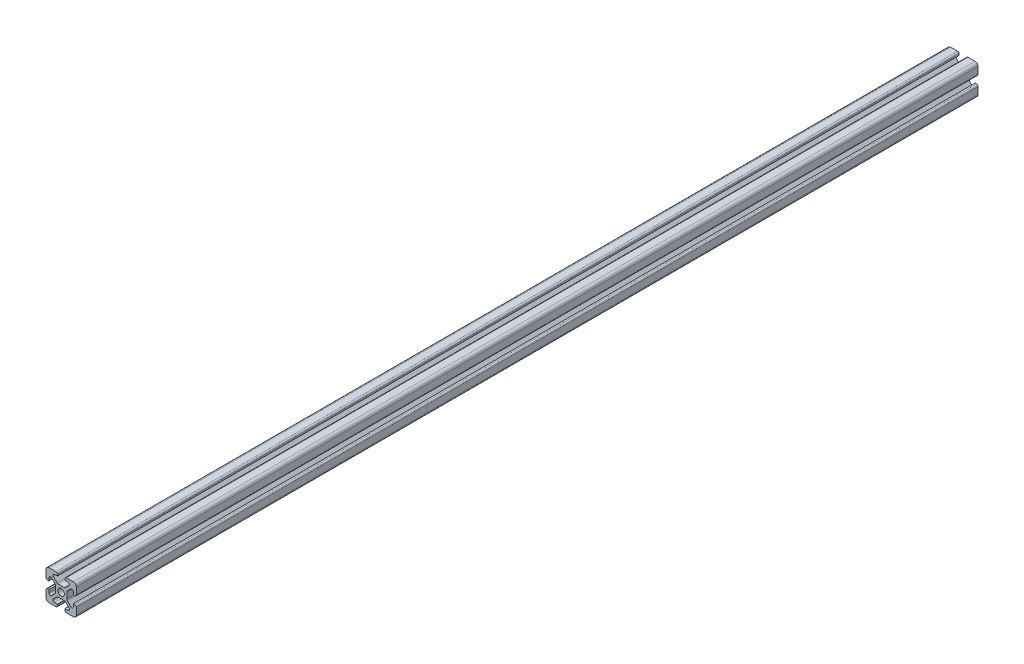
SolidWorks part; units mm, degrees
ref_plane "Front Plane" through (0, 0, 0) normal (0, 0, 1) x (1, 0, 0)
ref_plane "Top Plane" through (0, 0, 0) normal (0, 1, 0) x (1, 0, 0)
ref_plane "Right Plane" through (0, 0, 0) normal (1, 0, 0) x (0, 0, -1)
sketch "Sketch1" plane through (0, 0, 0) normal (0, 0, 1) x (1, 0, 0)
  line L0 (10.1, 10.1) -> (10.1, 0.1) construction
  line L1 (2, 0) -> (6.6, 0)
  line L2 (0, 2) -> (0, 6.6)
  line L3 (2, 20.2) -> (6.6, 20.2)
  line L4 (20.2, 2) -> (20.2, 6.6)
  line L5 (10.1, 10.1) -> (0, 10.1) construction
  line L6 (7.6, 19.2) -> (7.6, 18.2)
  line L7 (7.6, 18.2) -> (5.6642, 18.2)
  line L8 (4.9571, 16.4929) -> (7.3071, 14.1429)
  line L9 (8.0142, 13.85) -> (12.1858, 13.85)
  line L10 (12.8929, 14.1429) -> (15.2429, 16.4929)
  line L11 (14.5358, 18.2) -> (12.6, 18.2)
  line L12 (12.6, 18.2) -> (12.6, 19.2)
  line L13 (-250.157, -110.88) -> (53.1764, -110.88) construction
  line L14 (13.6, 20.2) -> (18.2, 20.2)
  line L15 (19.2, 12.6) -> (18.2, 12.6)
  line L16 (18.2, 12.6) -> (18.2, 14.5358)
  line L17 (16.4929, 15.2429) -> (14.1429, 12.8929)
  line L18 (13.85, 12.1858) -> (13.85, 8.0142)
  line L19 (14.1429, 7.3071) -> (16.4929, 4.9571)
  line L20 (18.2, 5.6642) -> (18.2, 7.6)
  line L21 (18.2, 7.6) -> (19.2, 7.6)
  line L22 (12.6, 1) -> (12.6, 2)
  line L23 (12.6, 2) -> (14.5358, 2)
  line L24 (15.2429, 3.7071) -> (12.8929, 6.0571)
  line L25 (12.1858, 6.35) -> (8.0142, 6.35)
  line L26 (7.3071, 6.0571) -> (4.9571, 3.7071)
  line L27 (5.6642, 2) -> (7.6, 2)
  line L28 (7.6, 2) -> (7.6, 1)
  line L29 (1, 7.6) -> (2, 7.6)
  line L30 (2, 7.6) -> (2, 5.6642)
  line L31 (3.7071, 4.9571) -> (6.0571, 7.3071)
  line L32 (6.35, 8.0142) -> (6.35, 12.1858)
  line L33 (6.0571, 12.8929) -> (3.7071, 15.2429)
  line L34 (2, 14.5358) -> (2, 12.6)
  line L35 (2, 12.6) -> (1, 12.6)
  line L36 (20.2, 13.6) -> (20.2, 18.2)
  line L37 (13.6, 0) -> (18.2, 0)
  line L38 (0, 13.6) -> (0, 18.2)
  circle A0 centre (10.1, 10.1) radius 2.15
  arc A1 (12.8929, 14.1429) -> (12.1858, 13.85) centre (12.1858, 14.85) cw
  arc A2 (8.0142, 13.85) -> (7.3071, 14.1429) centre (8.0142, 14.85) cw
  arc A3 (15.2429, 16.4929) -> (14.5358, 18.2) centre (14.5358, 17.2) ccw
  arc A4 (5.6642, 18.2) -> (4.9571, 16.4929) centre (5.6642, 17.2) ccw
  arc A5 (2, 0) -> (0, 2) centre (2, 2) cw
  arc A6 (18.2, 0) -> (20.2, 2) centre (18.2, 2) ccw
  arc A7 (20.2, 18.2) -> (18.2, 20.2) centre (18.2, 18.2) ccw
  arc A8 (2, 20.2) -> (0, 18.2) centre (2, 18.2) ccw
  arc A9 (18.2, 14.5358) -> (16.4929, 15.2429) centre (17.2, 14.5358) ccw
  arc A10 (13.85, 12.1858) -> (14.1429, 12.8929) centre (14.85, 12.1858) cw
  arc A11 (14.1429, 7.3071) -> (13.85, 8.0142) centre (14.85, 8.0142) cw
  arc A12 (16.4929, 4.9571) -> (18.2, 5.6642) centre (17.2, 5.6642) ccw
  arc A13 (14.5358, 2) -> (15.2429, 3.7071) centre (14.5358, 3) ccw
  arc A14 (12.1858, 6.35) -> (12.8929, 6.0571) centre (12.1858, 5.35) cw
  arc A15 (7.3071, 6.0571) -> (8.0142, 6.35) centre (8.0142, 5.35) cw
  arc A16 (4.9571, 3.7071) -> (5.6642, 2) centre (5.6642, 3) ccw
  arc A17 (2, 5.6642) -> (3.7071, 4.9571) centre (3, 5.6642) ccw
  arc A18 (6.35, 8.0142) -> (6.0571, 7.3071) centre (5.35, 8.0142) cw
  arc A19 (6.0571, 12.8929) -> (6.35, 12.1858) centre (5.35, 12.1858) cw
  arc A20 (3.7071, 15.2429) -> (2, 14.5358) centre (3, 14.5358) ccw
  arc A21 (20.2, 13.6) -> (19.2, 12.6) centre (19.2, 13.6) cw
  arc A22 (20.2, 6.6) -> (19.2, 7.6) centre (19.2, 6.6) ccw
  arc A23 (13.6, 0) -> (12.6, 1) centre (13.6, 1) cw
  arc A24 (7.6, 1) -> (6.6, 0) centre (6.6, 1) cw
  arc A25 (1, 7.6) -> (0, 6.6) centre (1, 6.6) ccw
  arc A26 (1, 12.6) -> (0, 13.6) centre (1, 13.6) cw
  arc A27 (7.6, 19.2) -> (6.6, 20.2) centre (6.6, 19.2) ccw
  arc A28 (13.6, 20.2) -> (12.6, 19.2) centre (13.6, 19.2) ccw
  point P21 (12.6, 13.85)
  point P24 (7.6, 13.85)
  point P31 (0, 0)
  point P36 (20.2, 20.2)
  point P39 (0, 20.2)
  point P91 (10.1, 10.1)
  point P105 (12.6, 20.2)
  dimension "D3" = 4.3
  dimension "D9" = 1
  dimension "D10" = 2
  dimension "D13" = 1
  dimension "D1" = 20.2
  dimension "D2" = 10.1
  dimension "D4" = 5
  dimension "D5" = 2.5
  dimension "D6" = 6.35
  dimension "D7" = 2
  dimension "D8" = 45
  dimension "D12" = 10.1
  dimension "D14" = 20.2
  dimension "D15" = 7.6
  dimension "D16" = 6.35
  dimension "D11" = 4
extrude "Boss-Extrude1" add sketch "Sketch1" along normal blind 600
